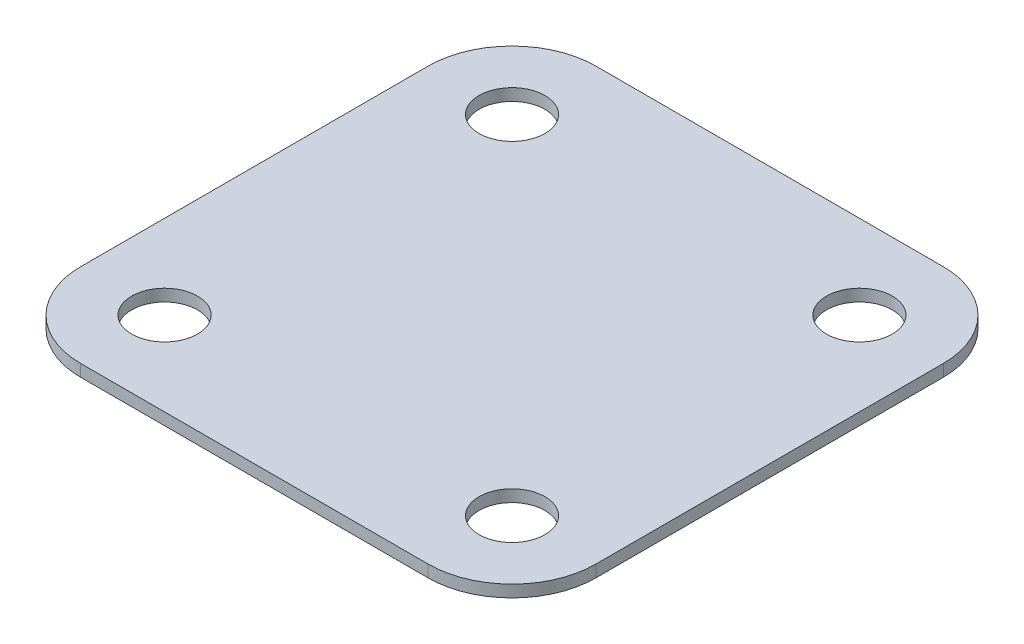
SolidWorks part; units mm, degrees
ref_plane "前视基准面" through (0, 0, 0) normal (0, 0, 1) x (1, 0, 0)
ref_plane "上视基准面" through (0, 0, 0) normal (0, 1, 0) x (1, 0, 0)
ref_plane "右视基准面" through (0, 0, 0) normal (1, 0, 0) x (0, 0, -1)
sketch "草图1" plane through (0, 0, 0) normal (0, 1, 0) x (1, 0, 0)
  line L1 (-43, 43) -> (43, 43)
  line L2 (-43, 43) -> (-43, -43)
  line L3 (-43, -43) -> (43, -43)
  line L4 (43, 43) -> (43, -43)
  line L5 (-43, 43) -> (43, -43) construction
  line L6 (-43, -43) -> (43, 43) construction
  point P0 (0, 0)
  dimension "D1" = 86
extrude "凸台-拉伸1" add sketch "草图1" along normal blind 2
fillet "圆角3" radius 14 4 edges at (-43, 1, 43) (43, 1, 43) (43, 1, -43) (-43, 1, -43)
sketch "草图2" plane through (0, 2, 0) normal (0, 1, 0) x (1, 0, 0)
  line L1 (-29, 29) -> (29, 29) construction
  line L2 (-29, 29) -> (-29, -29) construction
  line L3 (-29, -29) -> (29, -29) construction
  line L4 (29, 29) -> (29, -29) construction
  line L5 (-29, 29) -> (29, -29) construction
  line L6 (-29, -29) -> (29, 29) construction
  circle A0 centre (-29, 29) radius 5.5
  circle A1 centre (-29, -29) radius 5.5
  circle A2 centre (29, -29) radius 5.5
  circle A3 centre (29, 29) radius 5.5
  point P0 (0, 0)
  dimension "D2" = 11
  dimension "D1" = 58
extrude "切除-拉伸1" cut sketch "草图2" against normal through all both and the other way through all
